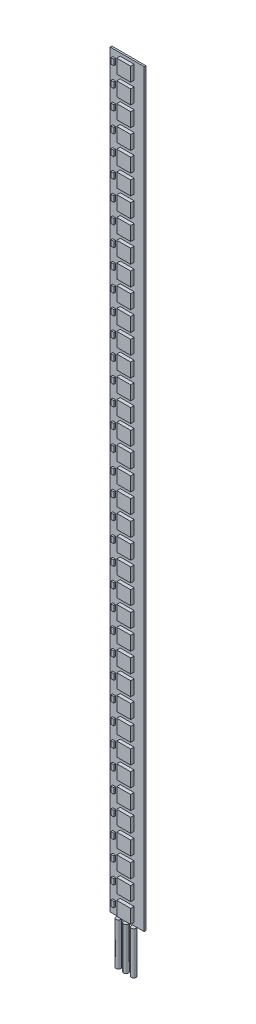
SolidWorks part; units mm, degrees
ref_plane "Plan de face" through (0, 0, 0) normal (0, 0, 1) x (1, 0, 0)
ref_plane "Plan de dessus" through (0, 0, 0) normal (0, 1, 0) x (1, 0, 0)
ref_plane "Plan de droite" through (0, 0, 0) normal (1, 0, 0) x (0, 0, -1)
sketch "Esquisse1" plane through (0, 0, 0) normal (0, 0, 1) x (1, 0, 0)
  line L1 (-6, 3.4722) -> (6, 3.4722)
  line L2 (-6, 3.4722) -> (-6, -3.4722)
  line L3 (-6, -3.4722) -> (6, -3.4722)
  line L4 (6, 3.4722) -> (6, -3.4722)
  point P4 (6, 0)
  point P6 (0, 3.4722)
  dimension "D1" = 6.9444
  dimension "D2" = 12
extrude "Boss.-Extru.1" add sketch "Esquisse1" along normal blind 0.6
sketch "Esquisse2" plane through (0, 0, 0.6) normal (0, 0, 1) x (1, 0, 0)
  line L1 (-2.45, -2.45) -> (2.45, -2.45)
  line L2 (-2.45, -2.45) -> (-2.45, 2.45)
  line L3 (-2.45, 2.45) -> (2.45, 2.45)
  line L4 (2.45, -2.45) -> (2.45, 2.45)
  point P4 (0, 2.45)
  point P6 (2.45, 0)
  dimension "D1" = 4.9
extrude "Boss.-Extru.2" add sketch "Esquisse2" along normal blind 1.2
sketch "Esquisse3" plane through (0, 0, 0.6) normal (0, 0, 1) x (1, 0, 0)
  line L0 (-2.45, 0) -> (-4.1, 0) construction
  line L1 (-5.1, 1) -> (-4.1, 1)
  line L2 (-5.1, 1) -> (-5.1, -1)
  line L3 (-5.1, -1) -> (-4.1, -1)
  line L4 (-4.1, 1) -> (-4.1, -1)
  line L5 (-2.45, 2.45) -> (-2.45, -2.45) construction
  point P6 (-4.6, 1)
  dimension "D1" = 4.6
  dimension "D2" = 2
  dimension "D3" = 1
extrude "Boss.-Extru.3" add sketch "Esquisse3" along normal blind 0.6
pattern_linear "Répétition linéaire1" count 38 spacing 6.9444 along (0, 1, 0) of "Boss.-Extru.2", "Boss.-Extru.3", "Boss.-Extru.1"
sketch "Esquisse4" plane through (0, -3.4722, 0) normal (0, -1, 0) x (1, 0, 0)
  line L0 (0, 0) -> (0, 1) construction
  circle A0 centre (-2.7, 0.9812) radius 0.85
  circle A1 centre (0, 1) radius 0.85
  circle A2 centre (2.7, 0.9812) radius 0.85
  dimension "D1" = 1.7
  dimension "D2" = 1
  dimension "D3" = 2.7
extrude "Boss.-Extru.4" add sketch "Esquisse4" along normal blind 15
equation "\"D1@Esquisse1\"=1000/144"
equation "\"D3@Répétition linéaire1\"=1000/144"
